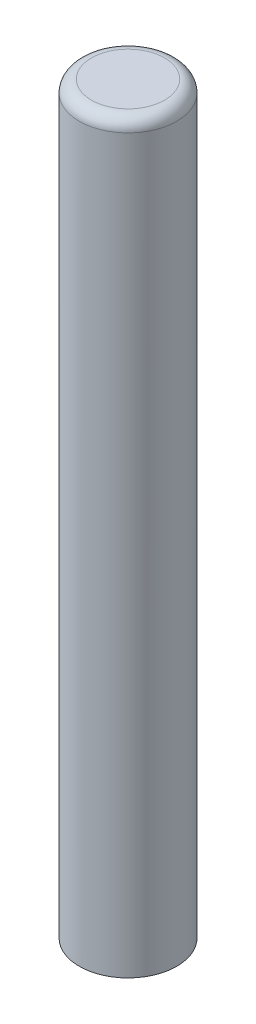
SolidWorks part; units mm, degrees
ref_plane "Front Plane" through (0, 0, 0) normal (0, 0, 1) x (1, 0, 0)
ref_plane "Top Plane" through (0, 0, 0) normal (0, 1, 0) x (1, 0, 0)
ref_plane "Right Plane" through (0, 0, 0) normal (1, 0, 0) x (0, 0, -1)
sketch "Sketch1" plane through (0, 0, 0) normal (0, 0, 1) x (1, 0, 0)
  line L0 (0, 0) -> (0, 110.138) construction
  line L1 (4, 61) -> (4, 0)
  line L2 (4, 0) -> (0, 0)
  line L3 (0, 0) -> (0, 61)
  line L4 (4, 61) -> (0, 61)
  dimension "D1" = 61
  dimension "D2" = 8
revolve "Revolve1" add sketch "Sketch1" angle 360 about L0
fillet "Fillet1" radius 1 1 edges at (0, 61, -4)
